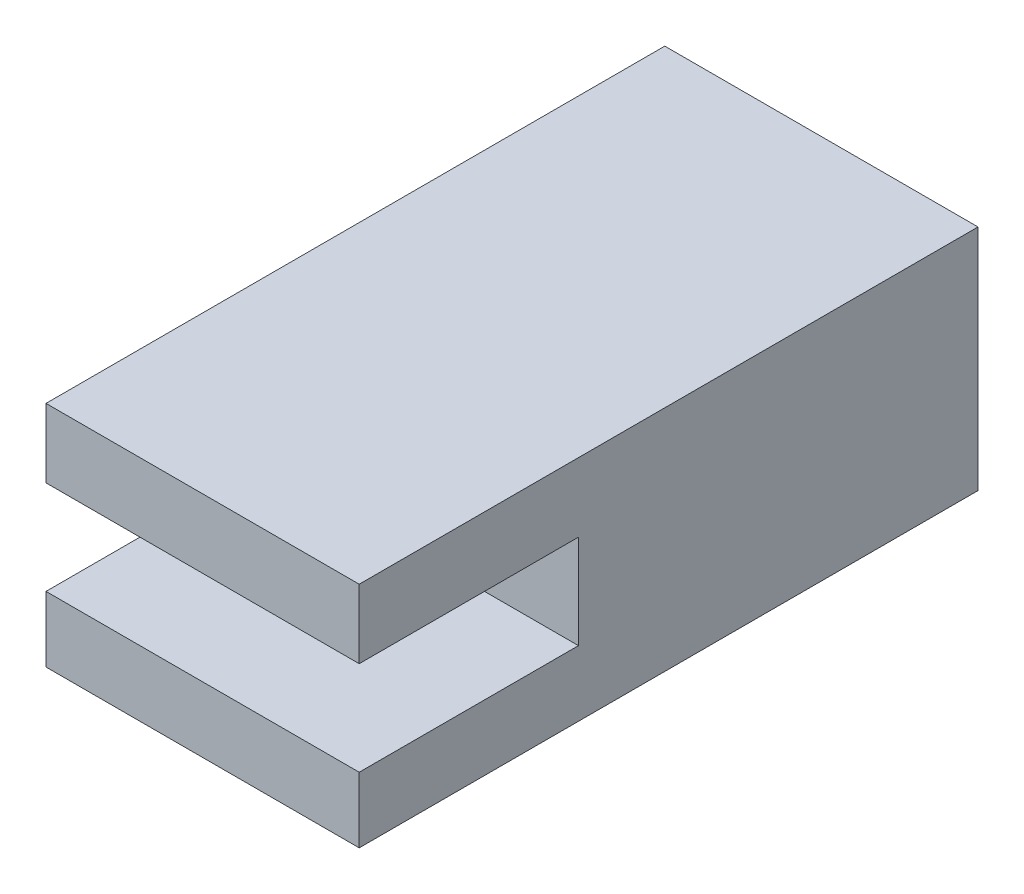
SolidWorks part; units mm, degrees
ref_plane "Front" through (0, 0, 0) normal (0, 0, 1) x (1, 0, 0)
ref_plane "Top" through (0, 0, 0) normal (0, 1, 0) x (1, 0, 0)
ref_plane "Right" through (0, 0, 0) normal (1, 0, 0) x (0, 0, -1)
sketch "草图1" plane through (0, 0, 0) normal (1, 0, 0) x (0, 0, -1)
  line L1 (0, 0) -> (10, 0)
  line L2 (0, 0) -> (0, 2.0922)
  line L3 (0, 2.0922) -> (10, 2.0922)
  line L4 (10, 0) -> (10, 2.0922)
  line L5 (10, 7.2908) -> (19.7563, 7.2908)
  line L6 (10, 2.0922) -> (10, 5.0922)
  line L7 (10, 5.0922) -> (10, 2.0922)
  line L8 (7, 2.0922) -> (7, 7.0922)
  line L9 (10, 5.0922) -> (0, 5.0922)
  line L10 (10, 5.0922) -> (10, 7.2908)
  line L11 (10, 7.2908) -> (0, 7.2908)
  line L12 (0, 5.0922) -> (0, 7.2908)
  line L13 (10, 5.0922) -> (10, 0)
  line L14 (10, 7.2908) -> (10, 0)
  line L15 (10, 0) -> (19.7563, 0)
  line L16 (19.7563, 7.2908) -> (19.7563, 0)
  dimension "D1" = 10
  dimension "D2" = 3
  dimension "D3" = 3
extrude "凸台-拉伸1" add sketch "草图1" along normal blind 10
sketch "草图2" plane through (0, 7.2908, 0) normal (0, 1, 0) x (1, 0, 0)
  line L0 (4.937, 10) -> (4.937, -0.1019) construction
sketch "草图4" plane through (0, 7.2908, 0) normal (0, 1, 0) x (1, 0, 0)
  circle A0 centre (5, 15.1298) radius 2
  point P2 (5, 15.1298)
  dimension "D1" = 4
